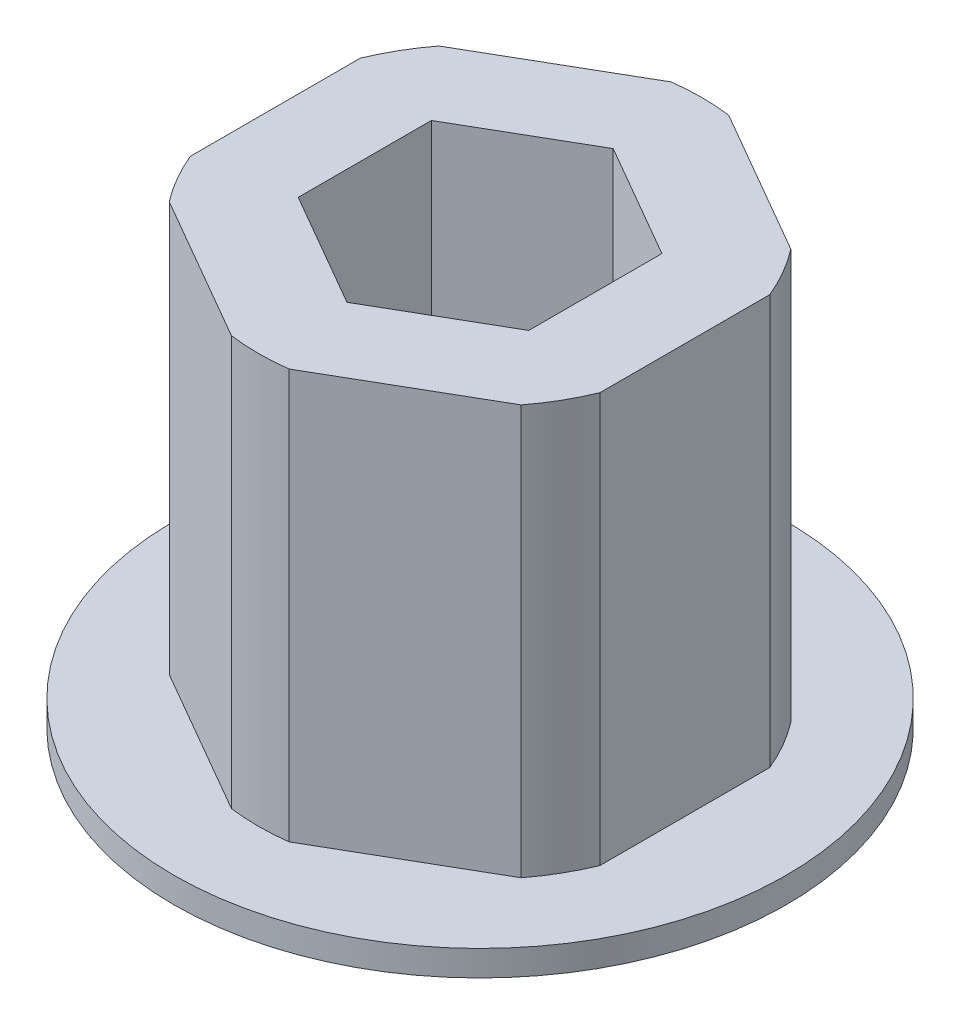
SolidWorks part; units mm, degrees
material "PET"
ref_plane "Front Plane" through (0, 0, 0) normal (0, 0, 1) x (1, 0, 0)
ref_plane "Top Plane" through (0, 0, 0) normal (0, 1, 0) x (1, 0, 0)
ref_plane "Right Plane" through (0, 0, 0) normal (1, 0, 0) x (0, 0, -1)
sketch "Sketch1" plane through (0, 0, 0) normal (0, 1, 0) x (1, 0, 0)
  line L1 (0, 4.1281) -> (-3.575, 2.064)
  line L2 (-3.575, 2.064) -> (-3.575, -2.064)
  line L3 (-3.575, -2.064) -> (0, -4.1281)
  line L4 (0, -4.1281) -> (3.575, -2.064)
  line L5 (3.575, -2.064) -> (3.575, 2.064)
  line L6 (3.575, 2.064) -> (0, 4.1281)
  circle A0 centre (0, 0) radius 9.5
  circle A1 centre (0, 0) radius 3.575 construction
  dimension "D1" = 7.15
  dimension "D2" = 19
extrude "Boss-Extrude1" add sketch "Sketch1" along normal blind 0.7937
sketch "Sketch2" plane through (0, 0.7937, 0) normal (0, 1, 0) x (1, 0, 0)
  line L1 (0, 7.3323) -> (-6.35, 3.6662)
  line L2 (-6.35, 3.6662) -> (-6.35, -3.6662)
  line L3 (-6.35, -3.6662) -> (0, -7.3323)
  line L4 (0, -7.3323) -> (6.35, -3.6662)
  line L5 (6.35, -3.6662) -> (6.35, 3.6662)
  line L6 (6.35, 3.6662) -> (0, 7.3323)
  circle A0 centre (0, 0) radius 6.35 construction
  circle A1 centre (0, 0) radius 6.875
  line M3 (-3.575, 2.064) -> (0, 4.1281)
  line M4 (0, 4.1281) -> (3.575, 2.064)
  line M5 (3.575, 2.064) -> (3.575, -2.064)
  line M6 (3.575, -2.064) -> (0, -4.1281)
  line M7 (0, -4.1281) -> (-3.575, -2.064)
  line M8 (-3.575, -2.064) -> (-3.575, 2.064)
  dimension "D1" = 12.7
  dimension "D2" = 13.75
extrude "Boss-Extrude2" add sketch "Sketch2" along normal blind 12.7 contours L4 A1 L5 L6 L1 L2 L3 M8 M3 M4 M5 M6 M7
